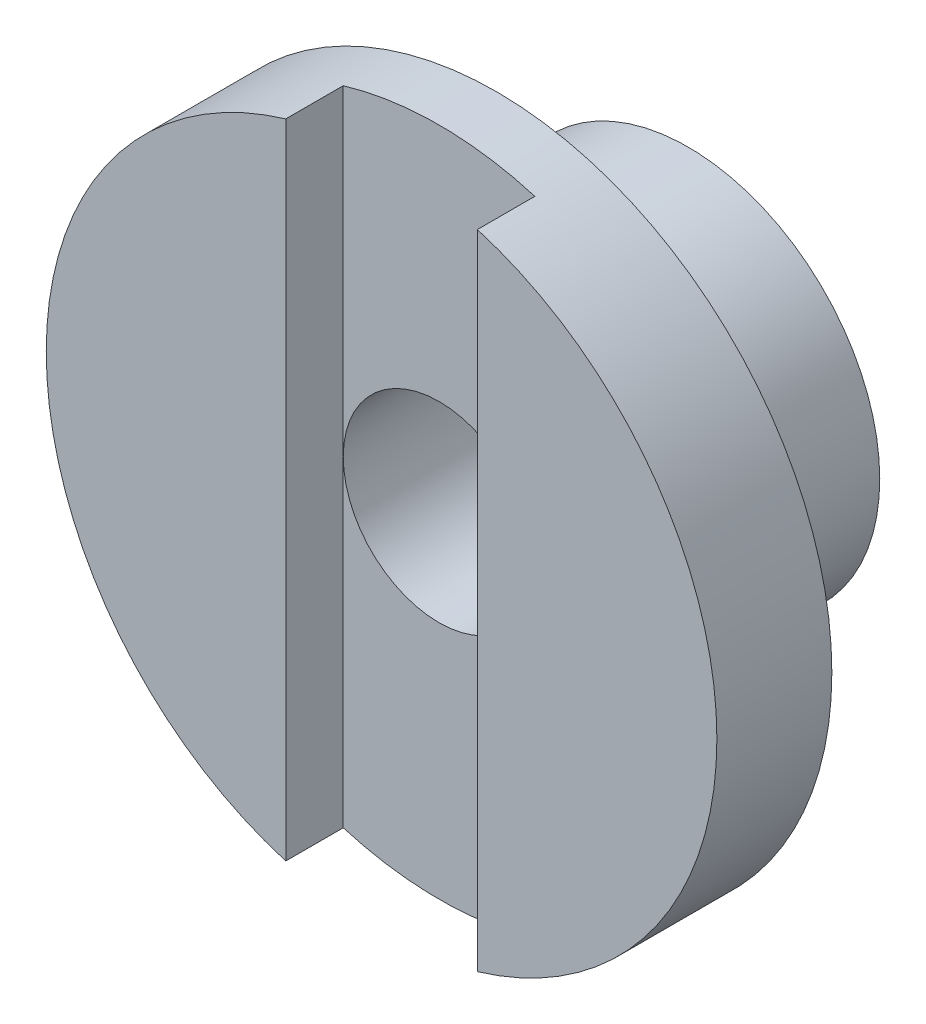
SolidWorks part; units mm, degrees
ref_plane "Front Plane" through (0, 0, 0) normal (0, 0, 1) x (1, 0, 0)
ref_plane "Top Plane" through (0, 0, 0) normal (0, 1, 0) x (1, 0, 0)
ref_plane "Right Plane" through (0, 0, 0) normal (1, 0, 0) x (0, 0, -1)
sketch "Sketch1" plane through (0, 0, 0) normal (0, 0, 1) x (1, 0, 0)
  line L0 (0, 45.4589) -> (0, -45.4589) construction
  line L1 (-65.1122, 0) -> (65.1122, 0) construction
  circle A0 centre (0, 0) radius 17.5
  point P4 (0, 0)
  point P7 (0, 0)
  dimension "D1" = 35
extrude "Boss-Extrude1" add sketch "Sketch1" along normal blind 6
sketch "Sketch2" plane through (0, 0, 6) normal (0, 0, 1) x (1, 0, 0)
  line L0 (0, 17.5) -> (0, -17.5) construction
  line L1 (-5, 16.7705) -> (-5, -16.7705)
  line L2 (5, 16.7705) -> (5, -16.7705)
  line L3 (-5, 17.5) -> (-5, -17.5) construction
  line L4 (5, 17.5) -> (5, -17.5) construction
  circle A0 centre (0, 0) radius 17.5 construction
  arc A1 (-5, -16.7705) -> (5, -16.7705) centre (0, 0) ccw
  arc A2 (5, 16.7705) -> (-5, 16.7705) centre (0, 0) ccw
  dimension "D1" = 5
  dimension "D2" = 5
extrude "Cut-Extrude1" cut sketch "Sketch2" against normal blind 3
sketch "Sketch3" plane through (0, 0, 6) normal (0, 0, 1) x (1, 0, 0)
  circle A0 centre (0, 0) radius 5
  dimension "D1" = 10
extrude "Cut-Extrude2" cut sketch "Sketch3" against normal blind 11
sketch "Sketch4" plane through (0, 0, 0) normal (0, 0, -1) x (-1, 0, 0)
  circle A0 centre (0, 0) radius 5
  circle A1 centre (0, 0) radius 10
  dimension "D1" = 20
  dimension "D2" = 10
extrude "Boss-Extrude2" add sketch "Sketch4" along normal blind 10
